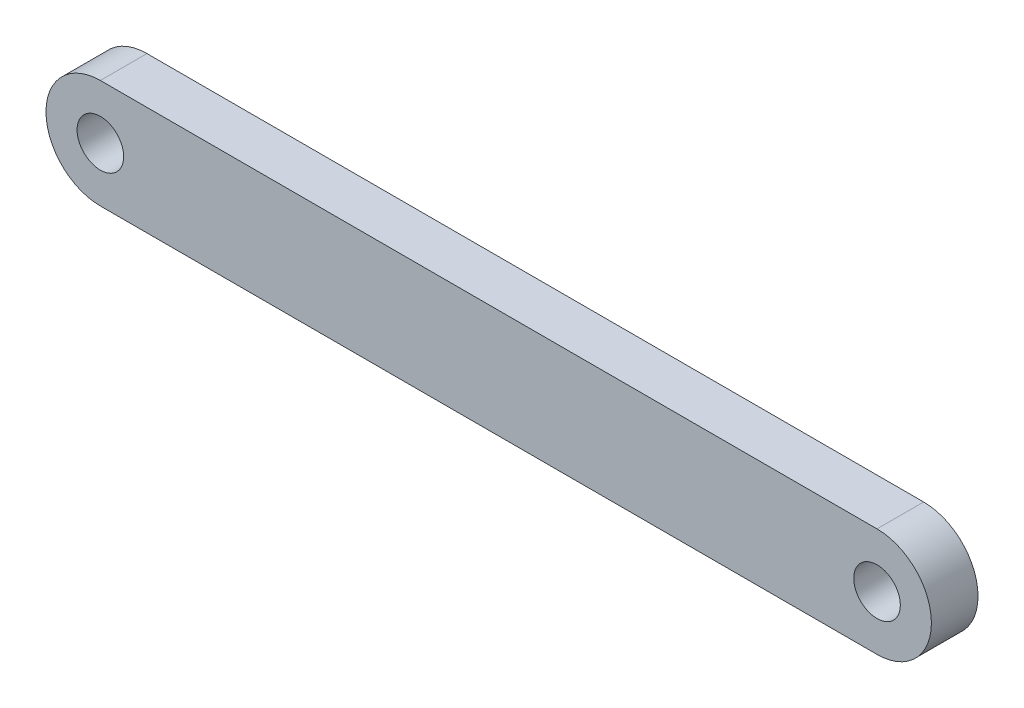
SolidWorks part; units mm, degrees
ref_plane "Front Plane" through (0, 0, 0) normal (0, 0, 1) x (1, 0, 0)
ref_plane "Top Plane" through (0, 0, 0) normal (0, 1, 0) x (1, 0, 0)
ref_plane "Right Plane" through (0, 0, 0) normal (1, 0, 0) x (0, 0, -1)
sketch "Sketch1" plane through (0, 0, 0) normal (0, 0, 1) x (1, 0, 0)
  line L0 (50.75, 28.5) -> (0.75, 28.5)
  line L1 (50.75, 35.5) -> (0.75, 35.5)
  line L2 (0.75, 35.5) -> (0.75, 28.5) construction
  circle A1 centre (50.75, 32) radius 1.5
  arc A2 (50.75, 35.5) -> (50.75, 28.5) centre (50.75, 32) cw
  circle A3 centre (0.75, 32) radius 1.5
  arc A4 (0.75, 28.5) -> (0.75, 35.5) centre (0.75, 32) cw
  dimension "D1" = 2
  dimension "D2" = 50
extrude "Boss-Extrude1" add sketch "Sketch1" along normal blind 3
